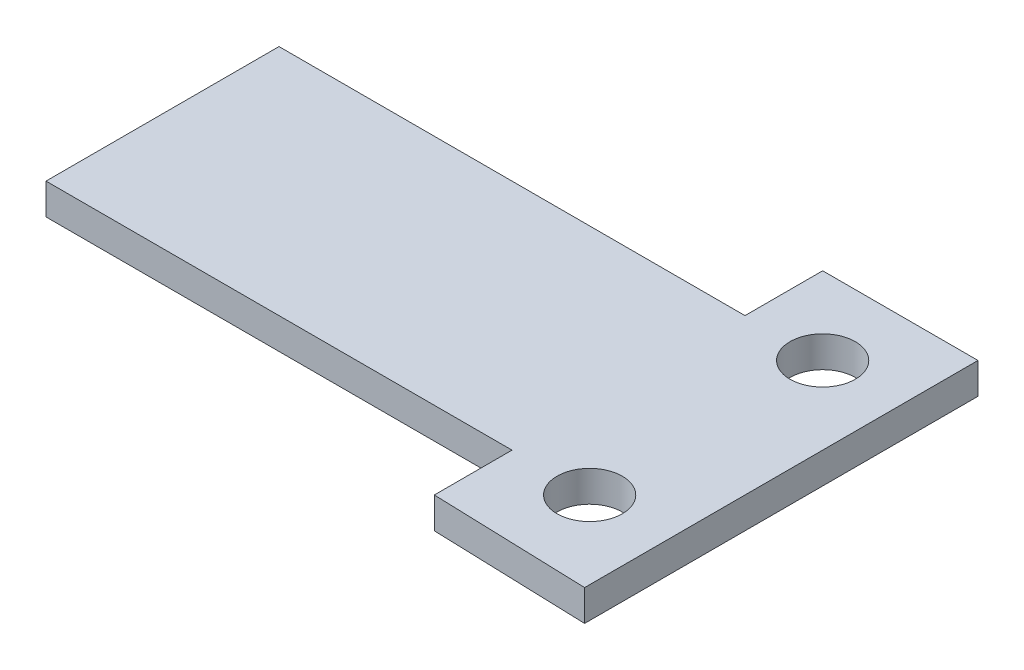
SolidWorks part; units mm, degrees
ref_plane "前视基准面" through (0, 0, 0) normal (0, 0, 1) x (1, 0, 0)
ref_plane "上视基准面" through (0, 0, 0) normal (0, 1, 0) x (1, 0, 0)
ref_plane "右视基准面" through (0, 0, 0) normal (1, 0, 0) x (0, 0, -1)
sketch "草图1" plane through (0, 0, 0) normal (0, 1, 0) x (1, 0, 0)
  line L0 (-5, 12.5) -> (5, 12.5)
  line L1 (-5, 12.5) -> (5, 12.5) construction
  line L2 (-5, 12.5) -> (-5, -12.5) construction
  line L3 (-5, -12.5) -> (5, -12.5) construction
  line L4 (5, 12.5) -> (5, -12.5) construction
  line L5 (0, -12.5) -> (0, 12.5) construction
  line L6 (-5, 0) -> (5, 0) construction
  line L7 (35, 7.5) -> (-35, 7.5) construction
  line L8 (35, 7.5) -> (35, -7.5) construction
  line L9 (35, -7.5) -> (-35, -7.5) construction
  line L10 (-35, 7.5) -> (-35, -7.5) construction
  line L11 (0, -7.5) -> (0, 7.5) construction
  line L12 (35, 0) -> (-35, 0) construction
  line L13 (5, 12.5) -> (5, -12.8264)
  line L14 (5, -12.8264) -> (-5, -12.5)
  line L15 (-5, -12.5) -> (-5, -7.5)
  line L16 (-5, -7.5) -> (-35, -7.5)
  line L17 (-35, -7.5) -> (-35, 7.5)
  line L18 (-35, 7.5) -> (-5, 7.5)
  line L19 (-5, 7.5) -> (-5, 12.5)
  circle A0 centre (0, 7.5) radius 2.1
  circle A1 centre (0, -7.5) radius 2.1
  point P0 (0, 0)
  point P4 (0, 0)
  point P8 (-5, -7.5)
  point P9 (-5, 5.9986)
  dimension "D1" = 10
  dimension "D2" = 25
  dimension "D3" = 15
  dimension "D4" = 30
extrude "凸台-拉伸1" add sketch "草图1" along normal blind 2
